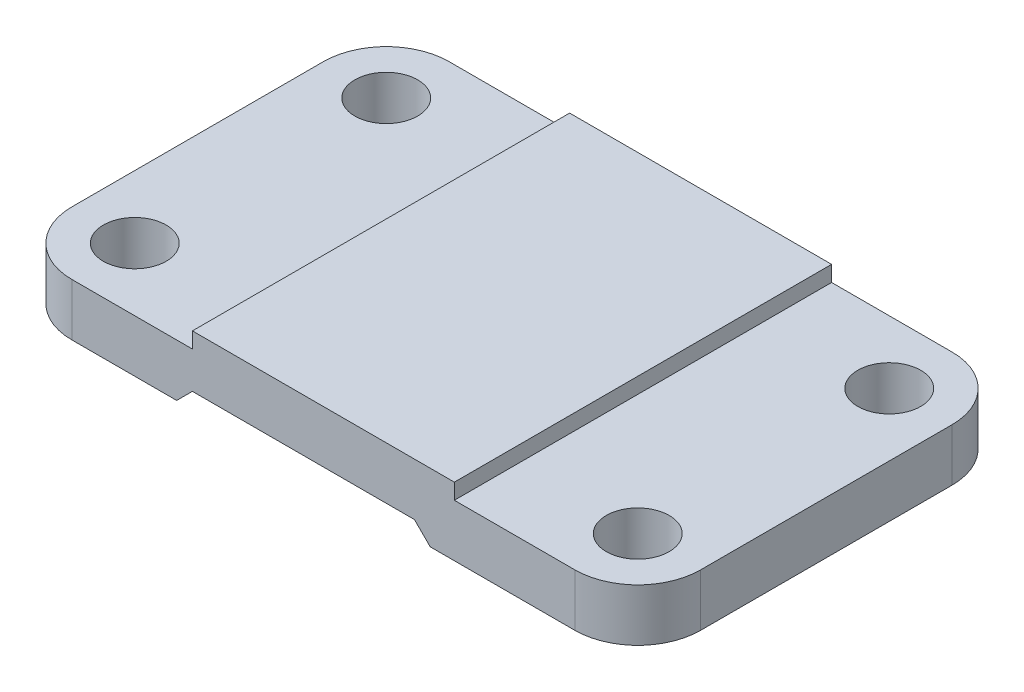
SolidWorks part; units mm, degrees
ref_plane "Front Plane" through (0, 0, 0) normal (0, 0, 1) x (1, 0, 0)
ref_plane "Top Plane" through (0, 0, 0) normal (0, 1, 0) x (1, 0, 0)
ref_plane "Right Plane" through (0, 0, 0) normal (1, 0, 0) x (0, 0, -1)
sketch "Sketch1" plane through (0, 0, 0) normal (0, 1, 0) x (1, 0, 0)
  line L1 (-60, -36) -> (60, -36)
  line L2 (-60, -36) -> (-60, 36)
  line L3 (-60, 36) -> (60, 36)
  line L4 (60, -36) -> (60, 36)
  line L5 (0, 36) -> (0, -36) construction
  line L6 (-60, 0) -> (60, 0) construction
  point P0 (0, 0)
  dimension "D1" = 72
  dimension "D2" = 120
extrude "Boss-Extrude1" add sketch "Sketch1" along normal blind 10
sketch "Sketch2" plane through (0, 10, 0) normal (0, 1, 0) x (1, 0, 0)
  circle A0 centre (-48, 24) radius 6
  circle A1 centre (-48, -24) radius 6
  circle A2 centre (48, -24) radius 6
  circle A3 centre (48, 24) radius 6
  dimension "D1" = 12
  dimension "D2" = 48
  dimension "D3" = 96
  dimension "D4" = 24
  dimension "D5" = 48
  dimension "D6" = 48
  dimension "D7" = 96
  dimension "D8" = 48
  dimension "D9" = 24
extrude "Cut-Extrude1" cut sketch "Sketch2" against normal through all
fillet "Fillet1" radius 12 4 edges at (60, 5, 36) (60, 5, -36) (-60, 5, 36) (-60, 5, -36)
sketch "Sketch3" plane through (0, 0, 36) normal (0, 0, 1) x (1, 0, 0)
  line L0 (-28, 0) -> (-25, 3)
  line L1 (-48, 0) -> (48, 0) construction
  line L2 (-25, 3) -> (17.3887, 3)
  line L3 (17.3887, 3) -> (20.3887, 0)
  line L4 (20.3887, 0) -> (-28, 0)
  dimension "D1" = 28
  dimension "D2" = 20.3887
  dimension "D3" = 48.3887
  dimension "D4" = 45
  dimension "D5" = 45
  dimension "D6" = 3
extrude "Cut-Extrude2" cut sketch "Sketch3" against normal through all
sketch "Sketch4" plane through (0, 10, 0) normal (0, 1, 0) x (1, 0, 0)
  line L1 (-25, -36) -> (25, -36)
  line L2 (-25, -36) -> (-25, 36)
  line L3 (-25, 36) -> (25, 36)
  line L4 (25, -36) -> (25, 36)
  line L5 (0, 36) -> (0, -36) construction
  line L6 (-25, 0) -> (25, 0) construction
  point P0 (0, 0)
  dimension "D1" = 50
  dimension "D2" = 72
extrude "Boss-Extrude3" add sketch "Sketch4" along normal blind 3
